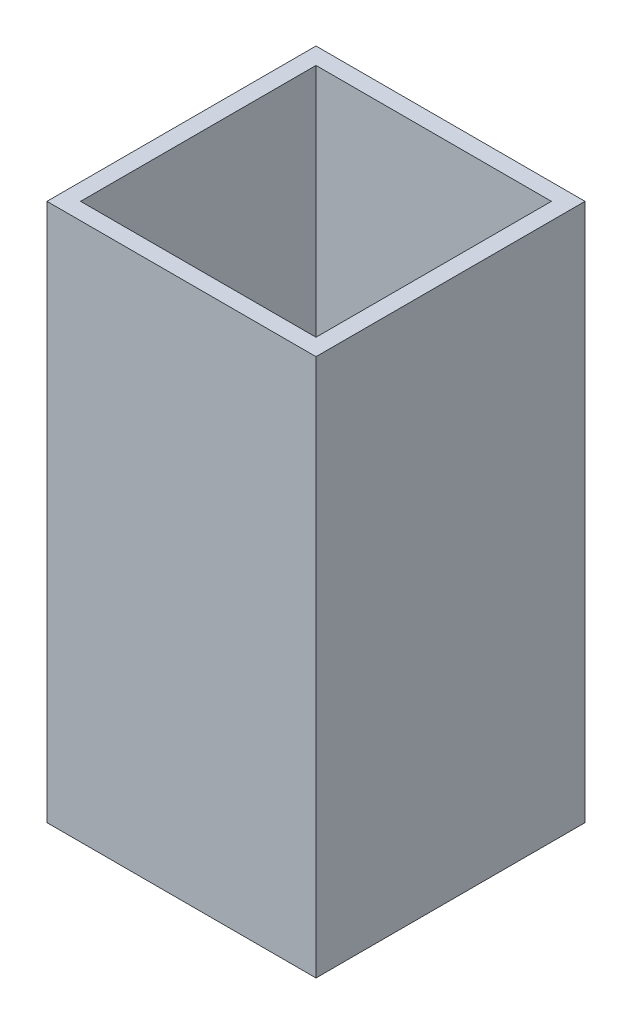
SolidWorks part; units mm, degrees
ref_plane "Front Plane" through (0, 0, 0) normal (0, 0, 1) x (1, 0, 0)
ref_plane "Top Plane" through (0, 0, 0) normal (0, 1, 0) x (1, 0, 0)
ref_plane "Right Plane" through (0, 0, 0) normal (1, 0, 0) x (0, 0, -1)
sketch "Sketch1" plane through (0, 0, 0) normal (0, 1, 0) x (1, 0, 0)
  line L1 (12.7, 12.7) -> (-12.7, 12.7)
  line L2 (12.7, 12.7) -> (12.7, -12.7)
  line L3 (12.7, -12.7) -> (-12.7, -12.7)
  line L4 (-12.7, 12.7) -> (-12.7, -12.7)
  line L5 (12.7, 12.7) -> (-12.7, -12.7) construction
  line L6 (12.7, -12.7) -> (-12.7, 12.7) construction
  line L7 (11.1125, 11.1125) -> (-11.1125, 11.1125)
  line L8 (11.1125, 11.1125) -> (11.1125, -11.1125)
  line L9 (11.1125, -11.1125) -> (-11.1125, -11.1125)
  line L10 (-11.1125, 11.1125) -> (-11.1125, -11.1125)
  line L11 (11.1125, 11.1125) -> (-11.1125, -11.1125) construction
  line L12 (11.1125, -11.1125) -> (-11.1125, 11.1125) construction
  point P1 (0, 0)
  point P6 (0, 0)
  dimension "D1" = 25.4
  dimension "D2" = 25.4
  dimension "D3" = 1.5875
  dimension "D4" = 1.5875
extrude "Boss-Extrude1" add sketch "Sketch1" along normal blind 50.8
